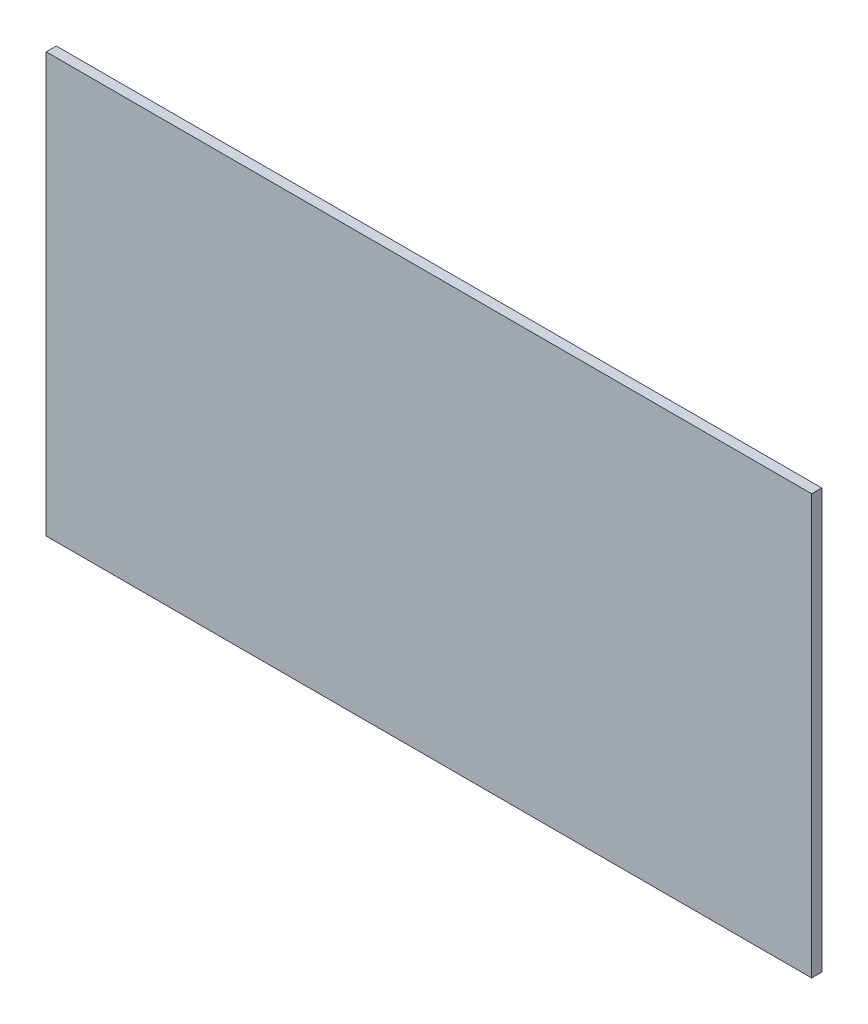
SolidWorks part; units mm, degrees
ref_plane "前视基准面" through (0, 0, 0) normal (0, 0, 1) x (1, 0, 0)
ref_plane "上视基准面" through (0, 0, 0) normal (0, 1, 0) x (1, 0, 0)
ref_plane "右视基准面" through (0, 0, 0) normal (1, 0, 0) x (0, 0, -1)
other "Configuration Table"
sketch "草图1" plane through (0, 0, 0) normal (0, 0, 1) x (1, 0, 0)
  line L1 (0, 0) -> (151.5, 0)
  line L2 (0, 0) -> (0, 83)
  line L3 (0, 83) -> (151.5, 83)
  line L4 (151.5, 0) -> (151.5, 83)
  dimension "D1" = 151.5
  dimension "D2" = 83
extrude "凸台-拉伸1" add sketch "草图1" along normal blind 2
